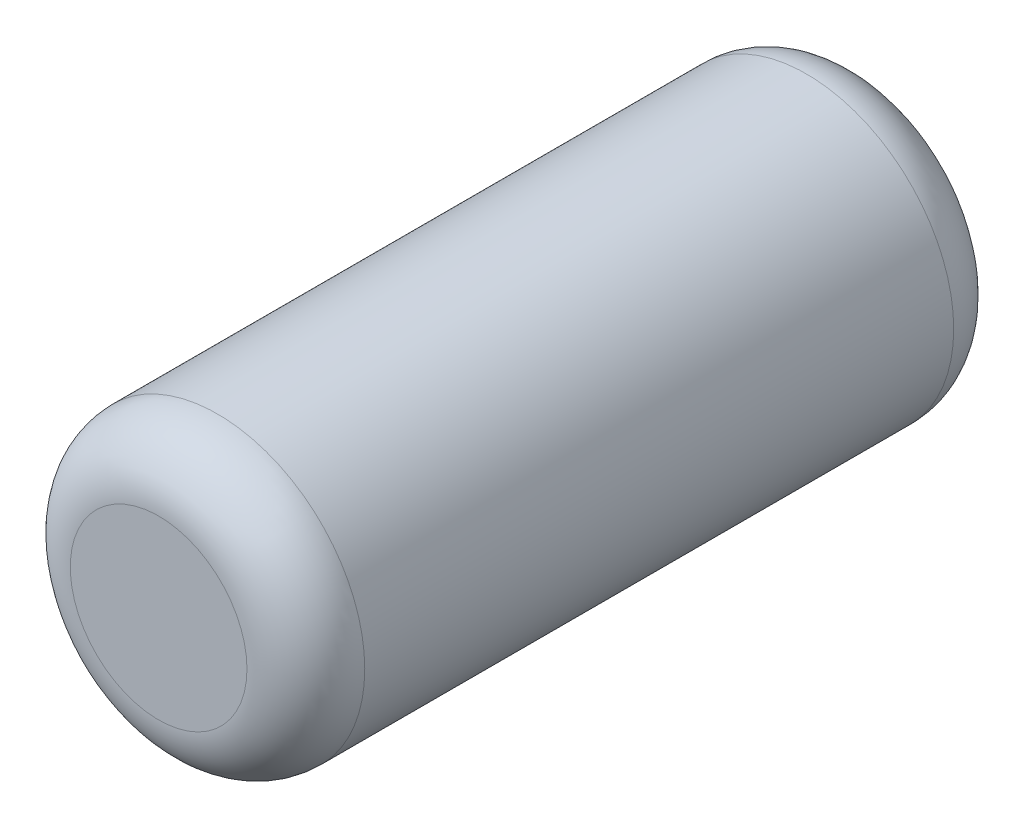
SolidWorks part; units mm, degrees
ref_plane "Front Plane" through (0, 0, 0) normal (1, 0, 0) x (0, 1, 0)
ref_plane "Top Plane" through (0, 0, 0) normal (0, 0, 1) x (0, 1, 0)
ref_plane "Right Plane" through (0, 0, 0) normal (0, 1, 0) x (-1, 0, 0)
sketch "Sketch1" plane through (0, 0, 0) normal (0, 0, 1) x (0, 1, 0)
  circle A0 centre (0, 0) radius 2.5
  dimension "D1" = 5
extrude "Boss-Extrude1" add sketch "Sketch1" against normal blind 12
fillet "Fillet1" radius 1 2 edges at (2.5, 0, -12) (2.5, 0, 0)
scale "Scale1" scale about centroid uniform scaling yes scale factor 0.7
